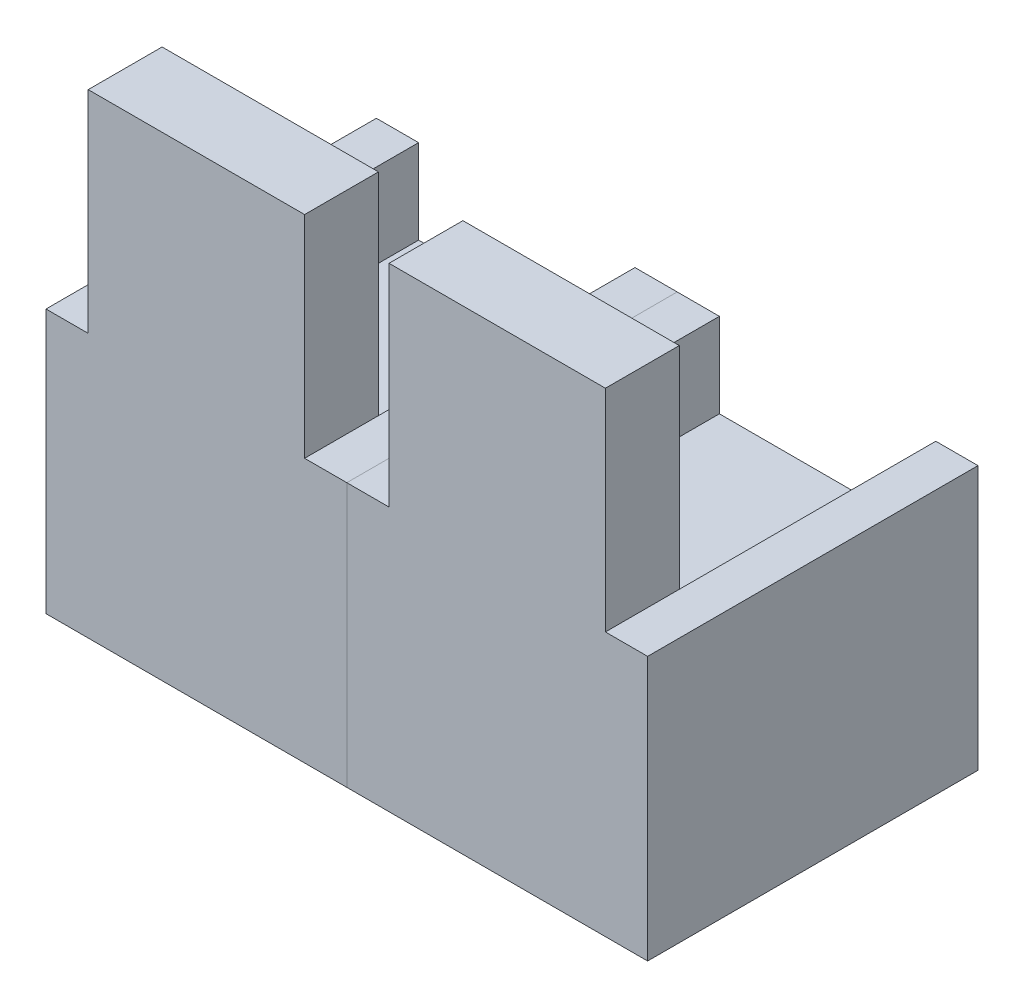
SolidWorks part; units mm, degrees
ref_plane "Front Plane" through (0, 0, 0) normal (0, 0, 1) x (1, 0, 0)
ref_plane "Top Plane" through (0, 0, 0) normal (0, 1, 0) x (1, 0, 0)
ref_plane "Right Plane" through (0, 0, 0) normal (1, 0, 0) x (0, 0, -1)
sketch "Sketch1" plane through (0, 0, 0) normal (0, 1, 0) x (1, 0, 0)
  line L1 (-395.8039, 0) -> (328.0961, 0)
  line L2 (-395.8039, 0) -> (-395.8039, -795.02)
  line L3 (-395.8039, -795.02) -> (328.0961, -795.02)
  line L4 (328.0961, 0) -> (328.0961, -795.02)
  dimension "D1" = 795.02
  dimension "D2" = 723.9
extrude "Boss-Extrude1" add sketch "Sketch1" along normal blind 431.8
sketch "Sketch2" plane through (0, 431.8, 0) normal (0, 1, 0) x (1, 0, 0)
  line L0 (-395.8039, -795.02) -> (328.0961, -795.02) construction
  line L1 (-395.8039, 0) -> (-294.2039, 0)
  line L2 (-395.8039, 0) -> (-395.8039, -795.02)
  line L3 (-395.8039, -795.02) -> (-294.2039, -795.02)
  line L4 (-294.2039, 0) -> (-294.2039, -795.02)
  line L6 (328.0961, 0) -> (226.4961, 0)
  line L7 (328.0961, 0) -> (328.0961, -795.02)
  line L8 (328.0961, -795.02) -> (226.4961, -795.02)
  line L9 (226.4961, 0) -> (226.4961, -795.02)
  dimension "D1" = 101.6
extrude "Boss-Extrude2" add sketch "Sketch2" along normal blind 203.2
sketch "Sketch3" plane through (0, 431.8, 0) normal (0, 1, 0) x (1, 0, 0)
  line L0 (-294.2039, -795.02) -> (-294.2039, 0) construction
  line L1 (-294.2039, -617.22) -> (226.4961, -617.22)
  line L2 (-294.2039, -617.22) -> (-294.2039, -795.02)
  line L3 (-294.2039, -795.02) -> (226.4961, -795.02)
  line L4 (226.4961, -617.22) -> (226.4961, -795.02)
  dimension "D1" = 177.8
extrude "Boss-Extrude3" add sketch "Sketch3" along normal blind 711.2
pattern_linear "LPattern1" count 2 spacing 723.9 along (1, 0, 0) of bodies 103
